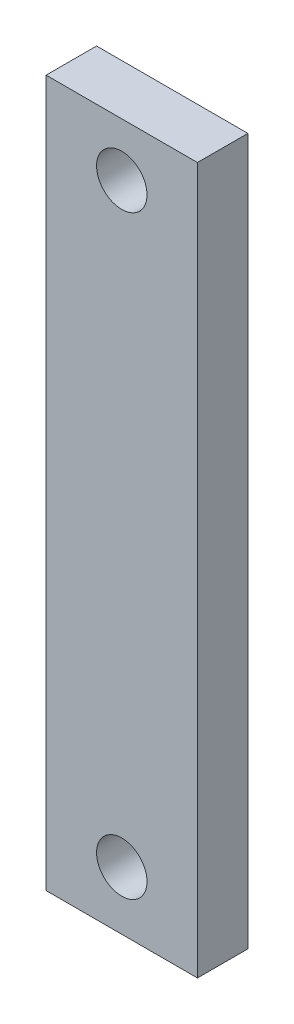
SolidWorks part; units mm, degrees
ref_plane "Front Plane" through (0, 0, 0) normal (0, 0, 1) x (1, 0, 0)
ref_plane "Top Plane" through (0, 0, 0) normal (0, 1, 0) x (1, 0, 0)
ref_plane "Right Plane" through (0, 0, 0) normal (1, 0, 0) x (0, 0, -1)
sketch "Sketch2" plane through (0, 0, 0) normal (0, 0, 1) x (1, 0, 0)
  line L1 (0, 0) -> (-38.1, 0)
  line L2 (0, 0) -> (0, 177.8)
  line L3 (0, 177.8) -> (-38.1, 177.8)
  line L4 (-38.1, 0) -> (-38.1, 177.8)
  dimension "D1" = 177.8
  dimension "D2" = 38.1
extrude "Boss-Extrude1" add sketch "Sketch2" along normal blind 12.7
sketch "Sketch3" plane through (0, 0, 12.7) normal (0, 0, 1) x (1, 0, 0)
  line L0 (-19.05, 177.8) -> (-19.05, 0) construction
  line L1 (0, 177.8) -> (-38.1, 177.8) construction
  line L2 (-38.1, 0) -> (0, 0) construction
sketch "Sketch4" plane through (0, 0, 12.7) normal (0, 0, 1) x (1, 0, 0)
  line L0 (-19.05, 177.8) -> (-19.05, 0) construction
  circle A0 centre (-19.05, 14.6575) radius 6.35
  dimension "D1" = 12.7
sketch "Sketch7" plane through (0, 0, 12.7) normal (0, 0, 1) x (1, 0, 0)
  line L0 (-19.05, 177.8) -> (-19.05, 0) construction
  circle A0 centre (-19.05, 164.3872) radius 6.35
  dimension "D1" = 12.7
extrude "Cut-Extrude1" cut sketch "Sketch7" against normal through all contours A0
extrude "Cut-Extrude2" cut sketch "Sketch4" against normal through all contours A0
